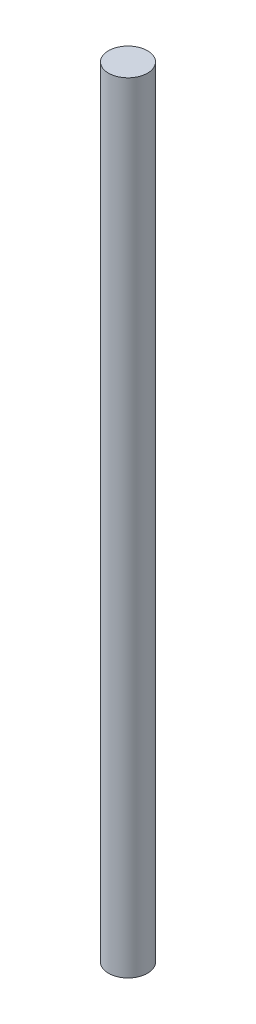
SolidWorks part; units mm, degrees
ref_plane "Front Plane" through (0, 0, 0) normal (0, 0, 1) x (1, 0, 0)
ref_plane "Top Plane" through (0, 0, 0) normal (0, 1, 0) x (1, 0, 0)
ref_plane "Right Plane" through (0, 0, 0) normal (1, 0, 0) x (0, 0, -1)
sketch "Sketch1" plane through (0, 0, 0) normal (0, 1, 0) x (1, 0, 0)
  circle A0 centre (0, 0) radius 1
  dimension "D1" = 2
extrude "Boss-Extrude1" add sketch "Sketch1" along normal mid plane 40
